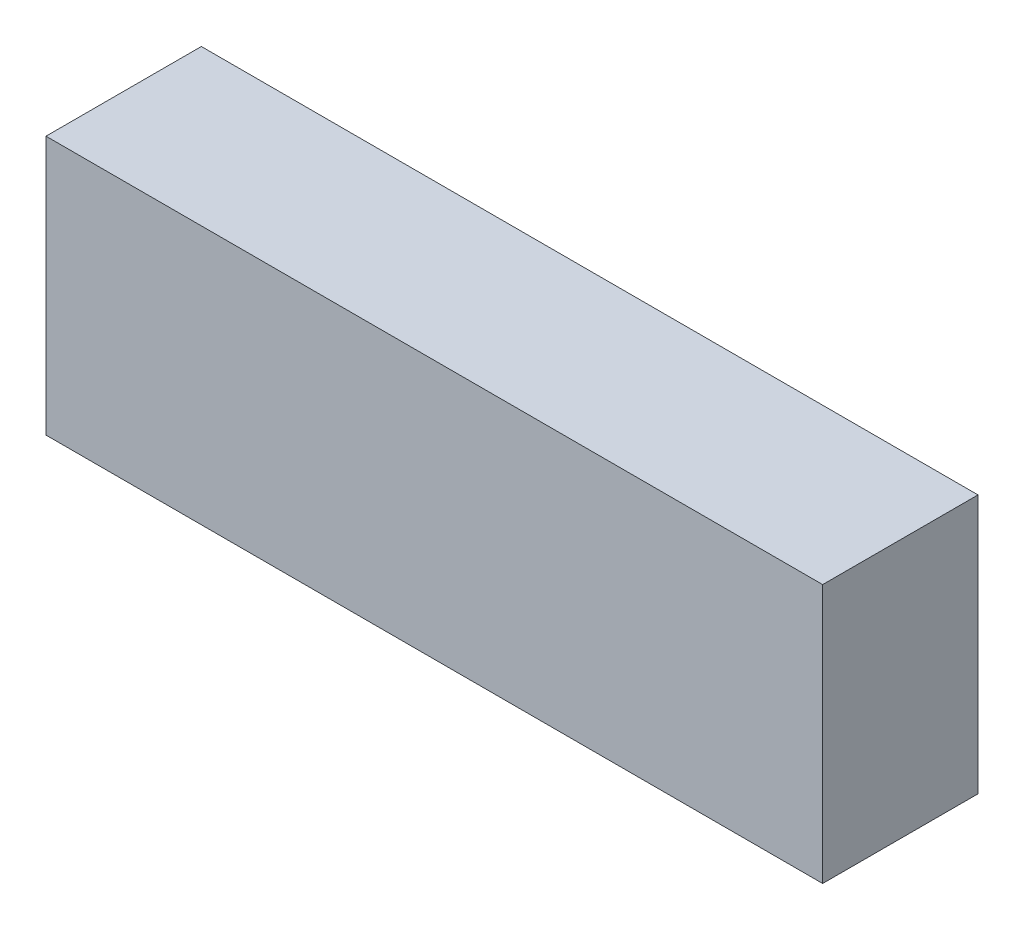
SolidWorks part; units mm, degrees
ref_plane "Front Plane" through (0, 0, 0) normal (0, 0, 1) x (1, 0, 0)
ref_plane "Top Plane" through (0, 0, 0) normal (0, 1, 0) x (1, 0, 0)
ref_plane "Right Plane" through (0, 0, 0) normal (1, 0, 0) x (0, 0, -1)
sketch "Sketch1" plane through (0, 0, 0) normal (0, 0, 1) x (1, 0, 0)
  line L1 (0, 0) -> (30, 0)
  line L2 (0, 0) -> (0, 10)
  line L3 (0, 10) -> (30, 10)
  line L4 (30, 0) -> (30, 10)
  dimension "D1" = 30
  dimension "D2" = 10
extrude "Boss-Extrude1" add sketch "Sketch1" along normal blind 6
